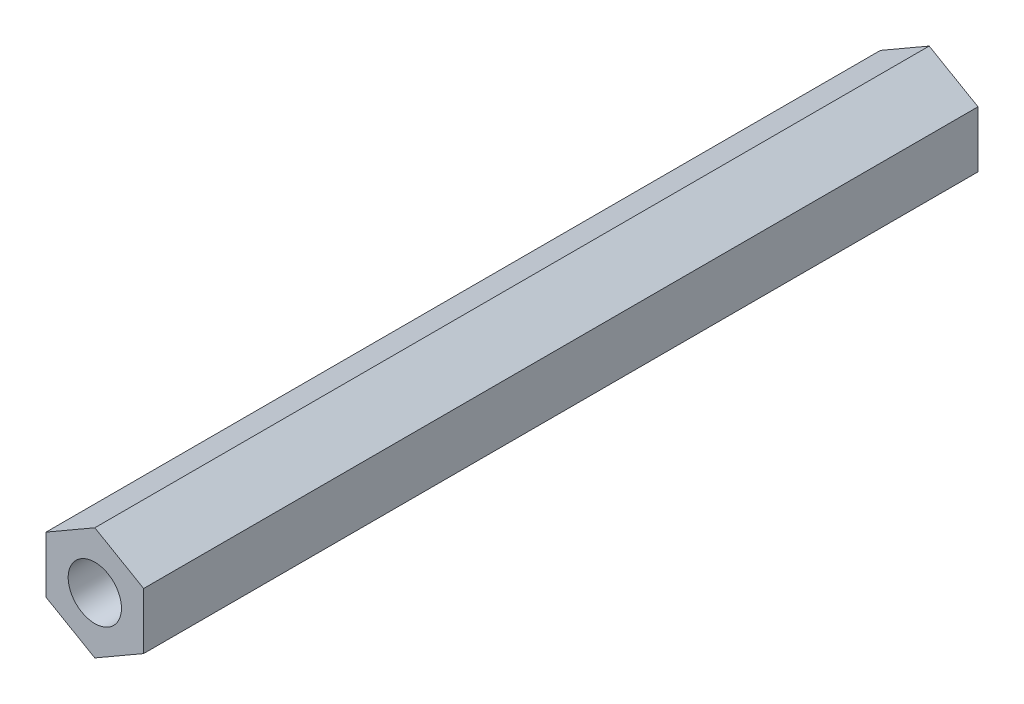
SolidWorks part; units mm, degrees
ref_plane "Plan de face" through (0, 0, 0) normal (0, 0, 1) x (1, 0, 0)
ref_plane "Plan de dessus" through (0, 0, 0) normal (0, 1, 0) x (1, 0, 0)
ref_plane "Plan de droite" through (0, 0, 0) normal (1, 0, 0) x (0, 0, -1)
sketch "Esquisse1" plane through (0, 0, 0) normal (0, 0, 1) x (1, 0, 0)
  line L1 (0, -3.1754) -> (2.75, -1.5877)
  line L2 (2.75, -1.5877) -> (2.75, 1.5877)
  line L3 (2.75, 1.5877) -> (0, 3.1754)
  line L4 (0, 3.1754) -> (-2.75, 1.5877)
  line L5 (-2.75, 1.5877) -> (-2.75, -1.5877)
  line L6 (-2.75, -1.5877) -> (0, -3.1754)
  circle A0 centre (0, 0) radius 2.75 construction
  circle A1 centre (0, 0) radius 1.5
  dimension "D2" = 3
  dimension "D1" = 5.5
extrude "Boss.-Extru.1" add sketch "Esquisse1" along normal blind 47
